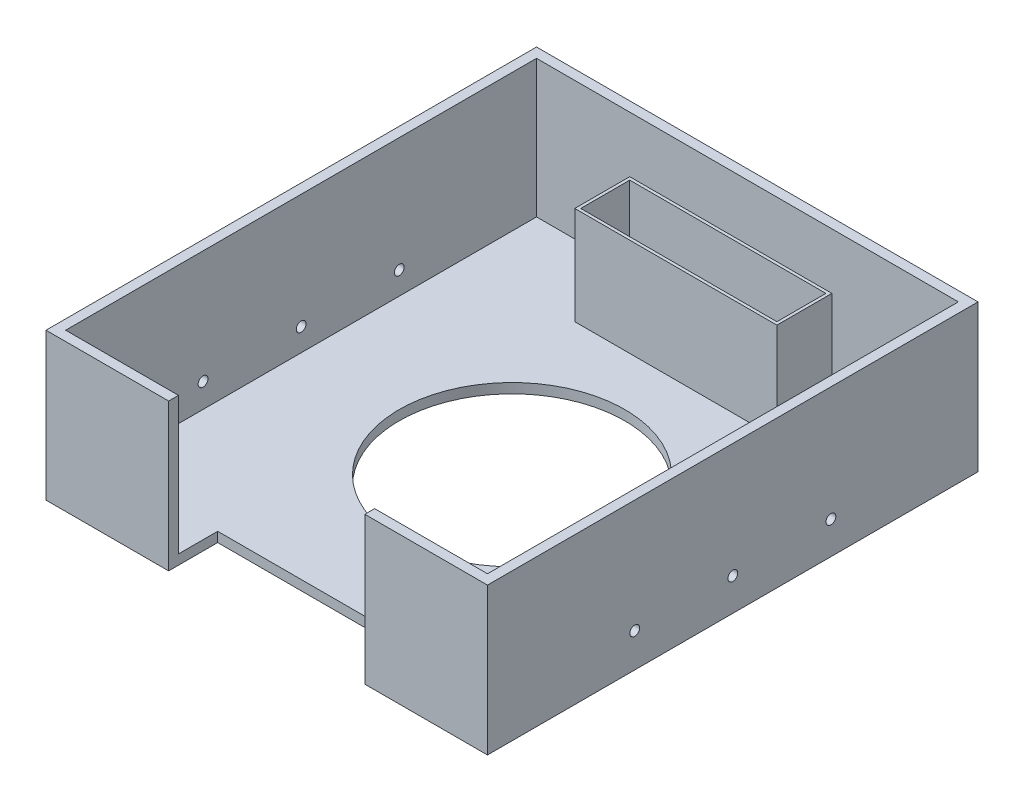
SolidWorks part; units mm, degrees
ref_plane "Front Plane" through (0, 0, 0) normal (0, 0, 1) x (1, 0, 0)
ref_plane "Top Plane" through (0, 0, 0) normal (0, 1, 0) x (1, 0, 0)
ref_plane "Right Plane" through (0, 0, 0) normal (1, 0, 0) x (0, 0, -1)
sketch "Sketch1" plane through (0, 0, 0) normal (0, 1, 0) x (1, 0, 0)
  line L0 (-225, 250) -> (225, 250)
  line L1 (-225, -250) -> (225, -250)
  line L2 (-225, -250) -> (-225, 250)
  line L4 (225, -250) -> (225, 250)
  point P0 (0, 0)
  dimension "D2" = 450
  dimension "D3" = 225
  dimension "D4" = 500
  dimension "D5" = 500
  dimension "D6" = 250
extrude "Boss-Extrude1" add sketch "Sketch1" along normal blind 10
sketch "Sketch2" plane through (0, 10, 0) normal (0, 1, 0) x (1, 0, 0)
  line L4 (215, -240) -> (215, 240)
  line L5 (215, 240) -> (-215, 240)
  line L6 (-215, 240) -> (-215, -240)
  line L7 (-215, -240) -> (215, -240)
  line L8 (225, -250) -> (225, 250)
  line L12 (225, 250) -> (-225, 250)
  line L18 (-225, 250) -> (-225, -250)
  line L19 (-225, -250) -> (225, -250)
  line L20 (225, -250) -> (225, 250)
  line L21 (225, 250) -> (-225, 250)
  line L22 (-225, 250) -> (-225, -250)
  line L23 (-225, -250) -> (225, -250)
  dimension "D1" = 0
  dimension "D2" = 10
extrude "Boss-Extrude2" add sketch "Sketch2" along normal blind 140
sketch "Sketch3" plane through (0, 10, 0) normal (0, 1, 0) x (1, 0, 0)
  circle A0 centre (0, 0) radius 115
extrude "Cut-Extrude1" cut sketch "Sketch3" against normal blind 10
sketch "Sketch5" plane through (0, 150, 0) normal (0, 1, 0) x (1, 0, 0)
  line L0 (-225, -250) -> (225, -250) construction
  line L1 (-100, -300) -> (100, -300)
  line L2 (-100, -300) -> (-100, -200)
  line L3 (-100, -200) -> (100, -200)
  line L4 (100, -300) -> (100, -200)
  line L5 (-100, -300) -> (100, -200) construction
  line L6 (-100, -200) -> (100, -300) construction
  point P0 (0, -250)
  dimension "D1" = 200
  dimension "D2" = 100
  dimension "D3" = 250
extrude "Cut-Extrude3" cut sketch "Sketch5" against normal through all
sketch "Sketch6" plane through (225, 0, 0) normal (1, 0, 0) x (0, 0, -1)
  line L2 (-250, 0) -> (250, 0) construction
  line L3 (-250, 150) -> (-250, 0) construction
  circle A0 centre (-99.9, 34.7) radius 5
  circle A1 centre (0.1, 33.13) radius 5
  circle A2 centre (100.1, 33.13) radius 5
  dimension "D5" = 100
  dimension "D1" = 150.1
  dimension "D2" = 33.13
  dimension "D3" = 33.13
  dimension "D4" = 100
  dimension "D6" = 34.7
extrude "Cut-Extrude4" cut sketch "Sketch6" against normal blind 10
sketch "Sketch7" plane through (-225, 0, 0) normal (-1, 0, 0) x (0, 0, 1)
  circle A12 centre (-100.1, 33.13) radius 5
  circle A13 centre (-0.1, 33.13) radius 5
  circle A14 centre (99.9, 34.7) radius 5
extrude "Cut-Extrude5" cut sketch "Sketch7" against normal blind 10
sketch "Sketch8" plane through (0, 10, 0) normal (0, 1, 0) x (1, 0, 0)
  line L0 (225, 250) -> (-225, 250) construction
  line L1 (-100, 220) -> (100, 220)
  line L2 (-100, 220) -> (-100, 170)
  line L3 (-100, 170) -> (100, 170)
  line L4 (100, 220) -> (100, 170)
  line L5 (-215, 240) -> (-215, -240) construction
  line L6 (215, -240) -> (215, 240) construction
  line L7 (-103, 223) -> (103, 223)
  line L8 (103, 223) -> (103, 167)
  line L9 (-103, 167) -> (103, 167)
  line L10 (-103, 223) -> (-103, 167)
  dimension "D1" = 30
  dimension "D2" = 50
  dimension "D3" = 50
  dimension "D4" = 200
  dimension "D5" = 115
  dimension "D6" = 115
  dimension "D7" = 3
extrude "Boss-Extrude3" add sketch "Sketch8" along normal blind 100
sketch "Sketch9" plane through (0, 0, 0) normal (0, -1, 0) x (1, 0, 0)
  line L0 (-225, -250) -> (-225, 250) construction
  line L1 (-201.8279, -145.9644) -> (-225, -145.9644)
  line L2 (-201.8279, -145.9644) -> (-201.8279, 145.9644)
  line L3 (-201.8279, 145.9644) -> (-225, 145.9644)
  line L5 (-201.8279, -145.9644) -> (-225, 0) construction
  line L6 (-201.8279, 145.9644) -> (-225, 0) construction
  line L7 (-225, 145.9644) -> (-225, -145.9644)
  line L8 (0, -82.5) -> (0, 82.5) construction
  line L9 (225, 145.9644) -> (225, -145.9644)
  line L10 (201.8279, -145.9644) -> (225, -145.9644)
  line L11 (201.8279, -145.9644) -> (201.8279, 145.9644)
  line L12 (201.8279, 145.9644) -> (225, 145.9644)
  point P0 (-225, 0)
split line "Split Line1"
